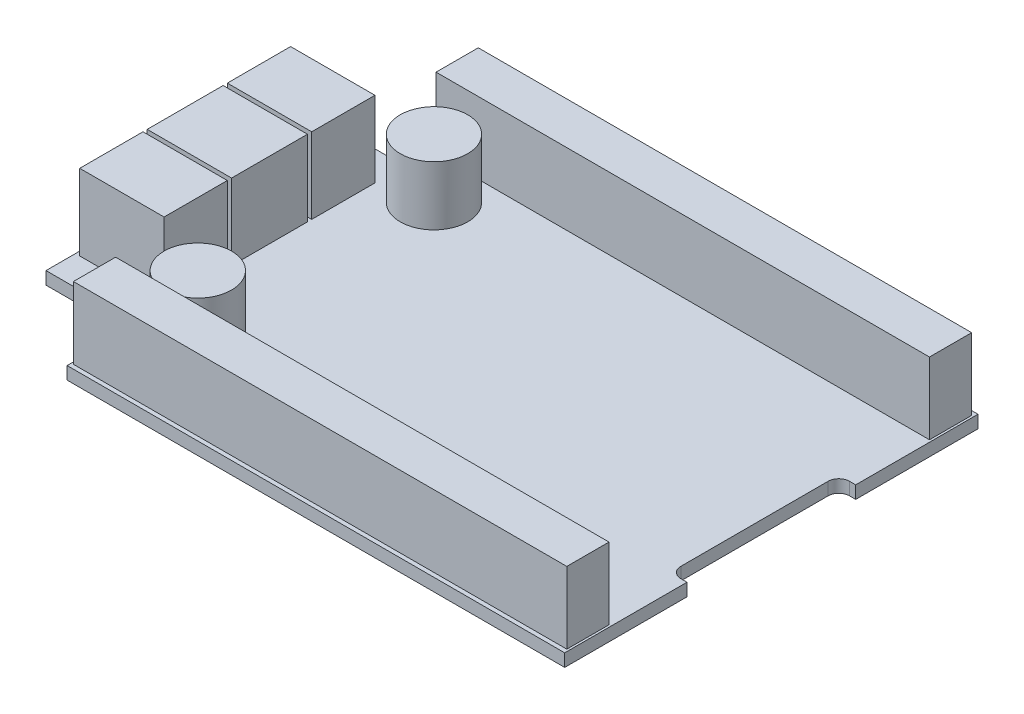
SolidWorks part; units mm, degrees
ref_plane "Front Plane" through (0, 0, 0) normal (0, 0, 1) x (1, 0, 0)
ref_plane "Top Plane" through (0, 0, 0) normal (0, 1, 0) x (1, 0, 0)
ref_plane "Right Plane" through (0, 0, 0) normal (1, 0, 0) x (0, 0, -1)
sketch "Sketch1" plane through (0, 0, 0) normal (0, 1, 0) x (1, 0, 0)
  line L0 (-29.0094, 25.8422) -> (29.9906, 25.8422)
  line L1 (29.9906, 25.8422) -> (29.9906, 11.3422)
  line L2 (29.9906, 11.3422) -> (27.9906, 11.3422)
  line L3 (27.9906, 11.3422) -> (27.9906, -8.6578)
  line L4 (27.9906, -8.6578) -> (29.9906, -8.6578)
  line L5 (29.9906, -8.6578) -> (29.9906, -23.1578)
  line L6 (29.9906, -23.1578) -> (-29.0094, -23.1578)
  line L7 (-29.0094, -23.1578) -> (-29.0094, -14.6578)
  line L8 (-29.0094, -14.6578) -> (-40.0094, -14.6578)
  line L9 (-40.0094, -14.6578) -> (-40.0094, 17.3422)
  line L10 (-40.0094, 17.3422) -> (-29.0094, 17.3422)
  line L11 (-29.0094, 17.3422) -> (-29.0094, 25.8422)
  line L13 (27.9906, 1.3422) -> (-40.0094, 1.3422) construction
  line L14 (-29.0094, 17.3422) -> (-29.0094, -14.6578) construction
  dimension "D1" = 59
  dimension "D2" = 59
  dimension "D3" = 14.5
  dimension "D4" = 14.5
  dimension "D5" = 20
  dimension "D6" = 70
  dimension "D7" = 32
  dimension "D8" = 40.0094
  dimension "D9" = 25.8422
  dimension "D10" = 2
extrude "Boss-Extrude1" add sketch "Sketch1" along normal blind 1.5
sketch "Sketch2" plane through (0, 1.5, 0) normal (0, 1, 0) x (1, 0, 0)
  line L0 (-29.0094, -23.1578) -> (29.9906, -23.1578) construction
  line L1 (-28.7594, -22.6578) -> (29.7394, -22.6578)
  line L2 (-28.7594, -22.6578) -> (-28.7594, -17.6566)
  line L3 (-28.7594, -17.6566) -> (29.7394, -17.6566)
  line L4 (29.7394, -22.6578) -> (29.7394, -17.6566)
  line L7 (-29.0094, -14.6578) -> (-29.0094, -23.1578) construction
  line L8 (27.9906, 1.3422) -> (-40.0094, 1.3422) construction
  line L9 (27.9906, -8.6578) -> (27.9906, 11.3422) construction
  line L10 (-40.0094, 17.3422) -> (-40.0094, -14.6578) construction
  line L11 (29.7394, 25.3422) -> (29.7394, 20.3409)
  line L12 (-28.7594, 20.3409) -> (29.7394, 20.3409)
  line L13 (-28.7594, 25.3422) -> (-28.7594, 20.3409)
  line L14 (-28.7594, 25.3422) -> (29.7394, 25.3422)
  dimension "D1" = 0.5
  dimension "D2" = 58.4987
  dimension "D3" = 0.25
  dimension "D4" = 5.0013
extrude "Boss-Extrude2" add sketch "Sketch2" along normal blind 8.5
sketch "Sketch3" plane through (0, 1.5, 0) normal (0, 1, 0) x (1, 0, 0)
  line L0 (-39.5094, 17.3422) -> (-39.5094, -14.6578) construction
  line L1 (-29.0094, 17.3422) -> (-40.0094, 17.3422) construction
  line L2 (-40.0094, -14.6578) -> (-29.0094, -14.6578) construction
  line L3 (-40.0094, 17.3422) -> (-40.0094, -14.6578) construction
  line L5 (-39.5094, 13.8422) -> (-29.5094, 13.8422)
  line L6 (-39.5094, 13.8422) -> (-39.5094, 6.3422)
  line L7 (-39.5094, 6.3422) -> (-29.5094, 6.3422)
  line L8 (-29.5094, 13.8422) -> (-29.5094, 6.3422)
  line L9 (-39.5094, 5.8422) -> (-29.5094, 5.8422)
  line L10 (-39.5094, 5.8422) -> (-39.5094, -3.1578)
  line L11 (-39.5094, -3.1578) -> (-29.5094, -3.1578)
  line L12 (-29.5094, 5.8422) -> (-29.5094, -3.1578)
  line L13 (-39.5094, -3.6578) -> (-29.5094, -3.6578)
  line L14 (-39.5094, -3.6578) -> (-39.5094, -11.1578)
  line L15 (-39.5094, -11.1578) -> (-29.5094, -11.1578)
  line L16 (-29.5094, -3.6578) -> (-29.5094, -11.1578)
  dimension "D1" = 0.5
  dimension "D2" = 3.5
  dimension "D3" = 7.5
  dimension "D4" = 0.5
  dimension "D5" = 0.5
  dimension "D6" = 3.5
  dimension "D7" = 7.5
  dimension "D8" = 10
extrude "Boss-Extrude3" add sketch "Sketch3" along normal blind 9
sketch "Sketch4" plane through (0, 1.5, 0) normal (0, 1, 0) x (1, 0, 0)
  line L0 (-24.0094, 15.3409) -> (-24.0094, -12.6566) construction
  line L1 (-28.7594, 20.3409) -> (29.7394, 20.3409) construction
  line L2 (29.7394, -17.6566) -> (-28.7594, -17.6566) construction
  line L3 (-29.0094, 25.8422) -> (-29.0094, 17.3422) construction
  circle A0 centre (-24.0094, 15.3409) radius 4
  circle A1 centre (-24.0094, -12.6566) radius 4
  dimension "D1" = 8
  dimension "D2" = 8
  dimension "D3" = 5
  dimension "D4" = 5
  dimension "D5" = 5
extrude "Boss-Extrude4" add sketch "Sketch4" along normal blind 7
fillet "Fillet1" radius 2.54 2 edges at (-29.0094, 0.75, -17.3422) (-29.0094, 0.75, 14.6578)
fillet "Fillet2" radius 1.27 2 edges at (27.9906, 0.75, 8.6578) (27.9906, 0.75, -11.3422)
equation "\"D6@Sketch3\"=\"D2@Sketch3\""
equation "\"D7@Sketch3\"=\"D3@Sketch3\""
equation "\"D4@Sketch4\"=\"D3@Sketch4\""
